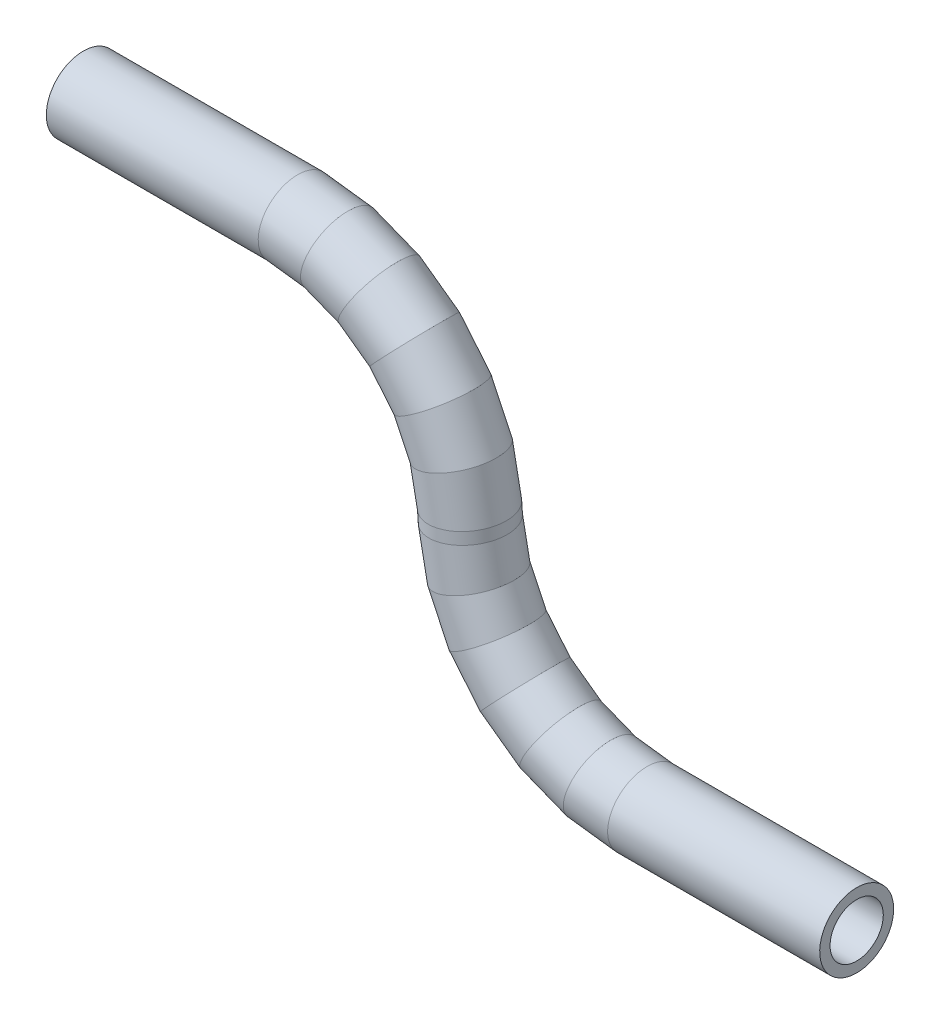
SolidWorks part; units mm, degrees
ref_plane "Front Plane" through (0, 0, 0) normal (0, 0, 1) x (1, 0, 0)
ref_plane "Top Plane" through (0, 0, 0) normal (0, 1, 0) x (1, 0, 0)
ref_plane "Right Plane" through (0, 0, 0) normal (1, 0, 0) x (0, 0, -1)
sketch3d "Path"
  line L0 (-2080.988, 33, 0) -> (-2099.188, 33, 0)
  line L1 (-2099.188, 33, 0) -> (-2102.9091, 33.4689, 0)
  line L2 (-2102.9091, 33.4689, 0) -> (-2106.3976, 34.8462, 0)
  line L3 (-2106.3976, 34.8462, 0) -> (-2109.4353, 37.0459, 0)
  line L4 (-2109.4353, 37.0459, 0) -> (-2111.8324, 39.9305, 0)
  line L5 (-2111.8324, 39.9305, 0) -> (-2113.439, 43.3195, 0)
  line L6 (-2113.439, 43.3195, 0) -> (-2114.1547, 47.0011, 0)
  line L7 (-2114.1547, 47.0011, 0) -> (-2114.2213, 47.9989, 0)
  line L8 (-2114.2213, 47.9989, 0) -> (-2114.9369, 51.6805, 0)
  line L9 (-2114.9369, 51.6805, 0) -> (-2116.5435, 55.0695, 0)
  line L10 (-2116.5435, 55.0695, 0) -> (-2118.9406, 57.9541, 0)
  line L11 (-2118.9406, 57.9541, 0) -> (-2121.9784, 60.1538, 0)
  line L12 (-2121.9784, 60.1538, 0) -> (-2125.4668, 61.5311, 0)
  line L13 (-2125.4668, 61.5311, 0) -> (-2129.188, 62, 0)
  line L14 (-2129.188, 62, 0) -> (-2147.388, 62, 0)
ref_plane "Start Plane" through (-2080.988, 0, 0) normal (1, 0, 0) x (0, 0, -1)
sketch "Profile" plane through (-2080.988, 0, 0) normal (1, 0, 0) x (0, 0, -1)
  circle A0 centre (0, 33) radius 3.175
  circle A1 centre (0, 33) radius 2.286
sweep "Tube" add profiles "Profile" path "Path"
